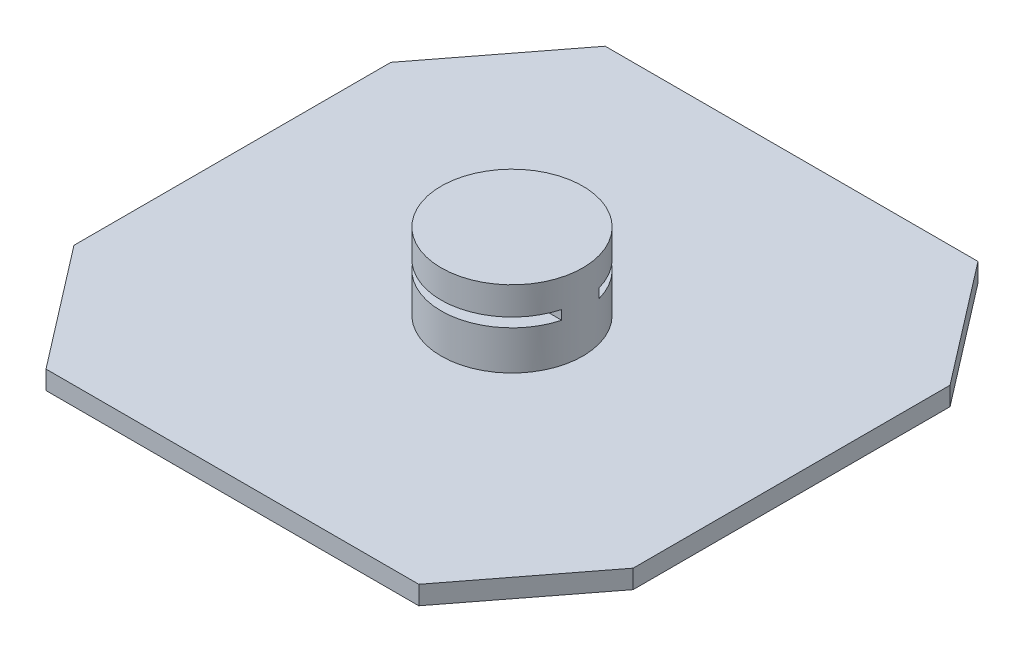
SolidWorks part; units mm, degrees
ref_plane "Front Plane" through (0, 0, 0) normal (0, 0, 1) x (1, 0, 0)
ref_plane "Top Plane" through (0, 0, 0) normal (0, 1, 0) x (1, 0, 0)
ref_plane "Right Plane" through (0, 0, 0) normal (1, 0, 0) x (0, 0, -1)
sketch "Sketch1" plane through (0, 0, 0) normal (0, 1, 0) x (1, 0, 0)
  line L0 (-100, 150) -> (-150, 85)
  line L1 (150, -150) -> (-150, -150) construction
  line L2 (150, -150) -> (150, 150) construction
  line L3 (150, 150) -> (-150, 150) construction
  line L4 (-150, -150) -> (-150, 150) construction
  line L5 (150, -150) -> (-150, 150) construction
  line L6 (150, 150) -> (-150, -150) construction
  line L7 (-150, -85) -> (-100, -150)
  line L8 (150, -85) -> (100, -150)
  line L9 (100, 150) -> (150, 85)
  line L10 (-100, 150) -> (100, 150)
  line L11 (150, 85) -> (150, -85)
  line L12 (100, -150) -> (-100, -150)
  line L13 (-150, -85) -> (-150, 85)
  point P0 (0, 0)
  dimension "D1" = 300
  dimension "D2" = 300
  dimension "D3" = 170
  dimension "D4" = 200
extrude "Boss-Extrude1" add sketch "Sketch1" along normal blind 10
sketch "Sketch2" plane through (0, 10, 0) normal (0, 1, 0) x (1, 0, 0)
  circle A0 centre (0, 0) radius 38
  dimension "D1" = 76
extrude "Boss-Extrude2" add sketch "Sketch2" along normal blind 41
sketch "Sketch3" plane through (0, 0, 0) normal (0, 0, 1) x (1, 0, 0)
  line L0 (-38, 51) -> (-38, 10) construction
  line L1 (-38, 36) -> (38, 36)
  line L2 (-38, 36) -> (-38, 31)
  line L3 (-38, 31) -> (38, 31)
  line L4 (38, 36) -> (38, 31)
  line L5 (38, 10) -> (38, 51) construction
  line L6 (38, 51) -> (-38, 51) construction
  dimension "D1" = 5
  dimension "D2" = 15
extrude "Cut-Extrude1" cut sketch "Sketch3" along normal blind 50 from offset 10
sketch "Sketch4" plane through (0, 0, 0) normal (0, 0, 1) x (1, 0, 0)
  line L4 (38, 36) -> (-38, 36)
  line L5 (38, 31) -> (38, 36)
  line L6 (-38, 31) -> (38, 31)
  line L7 (-38, 36) -> (-38, 31)
  line L8 (38, 36) -> (-38, 36)
  line L9 (38, 31) -> (38, 36)
  line L10 (-38, 31) -> (38, 31)
  line L11 (-38, 36) -> (-38, 31)
  dimension "D1" = 0
extrude "Cut-Extrude2" cut sketch "Sketch4" against normal blind 41 from offset 10
